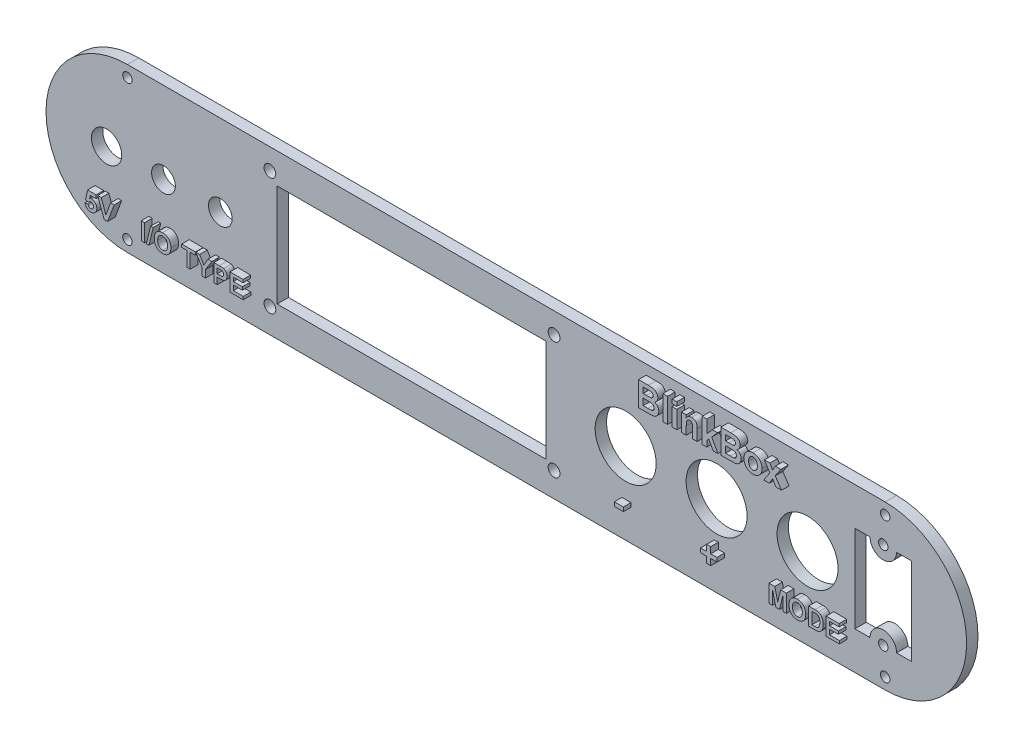
SolidWorks part; units mm, degrees
ref_plane "Front Plane" through (0, 0, 0) normal (0, 0, 1) x (1, 0, 0)
ref_plane "Top Plane" through (0, 0, 0) normal (0, 1, 0) x (1, 0, 0)
ref_plane "Right Plane" through (0, 0, 0) normal (1, 0, 0) x (0, 0, -1)
sketch "Sketch3" plane through (0, 0, 0) normal (0, 0, 1) x (1, 0, 0)
  circle A0 centre (0, 0) radius 2.5
  dimension "D1" = 5
sketch "Sketch1" plane through (0, 0, 0) normal (0, 0, 1) x (1, 0, 0)
  line L0 (-100, 0) -> (100, 0) construction
  line L1 (-100, 0) -> (100, 0) construction
  line L2 (-100, 21.5) -> (100, 21.5)
  line L3 (-100, -21.5) -> (100, -21.5)
  arc A0 (-100, 21.5) -> (-100, -21.5) centre (-100, 0) ccw
  arc A1 (100, -21.5) -> (100, 21.5) centre (100, 0) ccw
  point P2 (0, 0)
  dimension "D1" = 200
  dimension "D2" = 43
extrude "Boss-Extrude1" add sketch "Sketch1" along normal blind 3
sketch "Sketch2" plane through (0, 0, 3) normal (0, 0, 1) x (1, 0, 0)
  line L0 (-121.5, 0) -> (-105.5, 0) construction
  line L1 (-60.5, 13.5) -> (10.5, 13.5)
  line L2 (-60.5, 13.5) -> (-60.5, -13.5)
  line L3 (-60.5, -13.5) -> (10.5, -13.5)
  line L4 (10.5, 13.5) -> (10.5, -13.5)
  line L5 (-60.5, 13.5) -> (10.5, -13.5) construction
  line L6 (-60.5, -13.5) -> (10.5, 13.5) construction
  line L7 (-105.5, 0) -> (-90.5, 0) construction
  line L8 (-90.5, 0) -> (-75.5, 0) construction
  line L9 (-75.5, 0) -> (-60.5, 0) construction
  line L10 (31.5, 0) -> (55.5, 0) construction
  line L11 (55.5, 0) -> (79.5, 0) construction
  circle A0 centre (-105.5, 0) radius 4
  circle A1 centre (-90.5, 0) radius 3.135
  circle A2 centre (-75.5, 0) radius 3.135
  circle A3 centre (55.5, 0) radius 8.05
  circle A4 centre (31.5, 0) radius 8.05
  circle A5 centre (79.5, 0) radius 8.05
  arc A6 (-100, 21.5) -> (-100, -21.5) centre (-100, 0) ccw construction
  point P0 (-25, 0)
  dimension "D1" = 71
  dimension "D3" = 8
  dimension "D4" = 6.27
  dimension "D7" = 16.1
  dimension "D2" = 27
  dimension "D5" = 15
  dimension "D6" = 15
  dimension "D8" = 24
  dimension "D9" = 25
  dimension "D10" = 21
extrude "Cut-Extrude1" cut sketch "Sketch2" against normal through all both and the other way through all
sketch "Sketch4" plane through (0, 0, 3) normal (0, 0, 1) x (1, 0, 0)
  line L2 (-21.65, -11.5) -> (-28.15, -11.5)
  line L3 (-28.15, -12.5) -> (-21.65, -12.5)
  line L4 (15.1, 18.5) -> (-64.9, 18.5)
  line L5 (-64.9, 18.5) -> (-64.9, -17.5)
  line L6 (-64.9, -17.5) -> (15.1, -17.5)
  line L7 (15.1, -17.5) -> (15.1, 18.5)
  line L8 (15.1, 18.5) -> (-64.9, 18.5)
  line L9 (-64.9, 18.5) -> (-64.9, -17.5)
  line L10 (-64.9, -17.5) -> (15.1, -17.5)
  line L11 (15.1, -17.5) -> (15.1, 18.5)
  line L12 (-21.65, -11.5) -> (-28.15, -11.5)
  line L13 (-28.15, -12.5) -> (-21.65, -12.5)
  line L14 (7.35, 12.5) -> (0.85, 12.5)
  line L15 (0.85, 11.5) -> (7.35, 11.5)
  line L16 (7.35, 12.5) -> (0.85, 12.5)
  line L17 (0.85, 11.5) -> (7.35, 11.5)
  line L18 (7.35, -11.5) -> (0.85, -11.5)
  line L19 (0.85, -12.5) -> (7.35, -12.5)
  line L20 (7.35, -11.5) -> (0.85, -11.5)
  line L21 (0.85, -12.5) -> (7.35, -12.5)
  line L22 (-50.65, -11.5) -> (-57.15, -11.5)
  line L23 (-57.15, -12.5) -> (-50.65, -12.5)
  line L24 (-50.65, -11.5) -> (-57.15, -11.5)
  line L25 (-57.15, -12.5) -> (-50.65, -12.5)
  line L26 (-21.65, 12.5) -> (-28.15, 12.5)
  line L27 (-28.15, 11.5) -> (-21.65, 11.5)
  line L28 (-21.65, 12.5) -> (-28.15, 12.5)
  line L29 (-28.15, 11.5) -> (-21.65, 11.5)
  line L30 (-50.65, 12.5) -> (-57.15, 12.5)
  line L31 (-57.15, 11.5) -> (-50.65, 11.5)
  line L32 (-50.65, 12.5) -> (-57.15, 12.5)
  line L33 (-57.15, 11.5) -> (-50.65, 11.5)
  line L48 (10.5, 13.5) -> (-60.5, 13.5) construction
  line L49 (-60.5, 13.5) -> (-60.5, -13.5) construction
  circle A0 centre (-90.5, 0) radius 7
  circle A1 centre (-105.5, 0) radius 5.5
  circle A2 centre (-105.5, 0) radius 4 construction
  circle A3 centre (-75.5, 0) radius 5
  circle A4 centre (-75.5, 0) radius 3.135 construction
  circle A6 centre (12.6, -15) radius 1.25
  circle A7 centre (12.6, -15) radius 1.25
  circle A8 centre (12.6, 16) radius 1.25
  circle A9 centre (12.6, 16) radius 1.25
  circle A10 centre (-62.4, -15) radius 1.25
  circle A11 centre (-62.4, -15) radius 1.25
  circle A12 centre (-62.4, 16) radius 1.25
  circle A13 centre (-62.4, 16) radius 1.25
  circle A14 centre (-39.12, 16) radius 0.5
  circle A15 centre (-39.12, 16) radius 0.5
  circle A16 centre (-41.66, 16) radius 0.5
  circle A17 centre (-41.66, 16) radius 0.5
  circle A18 centre (-44.2, 16) radius 0.5
  circle A19 centre (-44.2, 16) radius 0.5
  circle A20 centre (-46.74, 16) radius 0.5
  circle A21 centre (-46.74, 16) radius 0.5
  circle A22 centre (-49.28, 16) radius 0.5
  circle A23 centre (-49.28, 16) radius 0.5
  circle A24 centre (-51.82, 16) radius 0.5
  circle A25 centre (-51.82, 16) radius 0.5
  circle A26 centre (-54.36, 16) radius 0.5
  circle A27 centre (-54.36, 16) radius 0.5
  circle A28 centre (-56.9, 16) radius 0.5
  circle A29 centre (-56.9, 16) radius 0.5
  circle A30 centre (-18.8, 16) radius 0.5
  circle A31 centre (-18.8, 16) radius 0.5
  circle A32 centre (-21.34, 16) radius 0.5
  circle A33 centre (-21.34, 16) radius 0.5
  circle A34 centre (-23.88, 16) radius 0.5
  circle A35 centre (-23.88, 16) radius 0.5
  circle A36 centre (-26.42, 16) radius 0.5
  circle A37 centre (-26.42, 16) radius 0.5
  circle A38 centre (-28.96, 16) radius 0.5
  circle A39 centre (-28.96, 16) radius 0.5
  circle A40 centre (-31.5, 16) radius 0.5
  circle A41 centre (-31.5, 16) radius 0.5
  circle A42 centre (-34.04, 16) radius 0.5
  circle A43 centre (-34.04, 16) radius 0.5
  circle A44 centre (-36.58, 16) radius 0.5
  circle A45 centre (-36.58, 16) radius 0.5
  arc A47 (-21.65, -12.5) -> (-21.65, -11.5) centre (-21.65, -12) ccw
  arc A48 (-28.15, -11.5) -> (-28.15, -12.5) centre (-28.15, -12) ccw
  arc A49 (-21.65, -12.5) -> (-21.65, -11.5) centre (-21.65, -12) ccw
  arc A50 (-28.15, -11.5) -> (-28.15, -12.5) centre (-28.15, -12) ccw
  arc A51 (7.35, 11.5) -> (7.35, 12.5) centre (7.35, 12) ccw
  arc A52 (0.85, 12.5) -> (0.85, 11.5) centre (0.85, 12) ccw
  arc A53 (7.35, 11.5) -> (7.35, 12.5) centre (7.35, 12) ccw
  arc A54 (0.85, 12.5) -> (0.85, 11.5) centre (0.85, 12) ccw
  arc A55 (7.35, -12.5) -> (7.35, -11.5) centre (7.35, -12) ccw
  arc A56 (0.85, -11.5) -> (0.85, -12.5) centre (0.85, -12) ccw
  arc A57 (7.35, -12.5) -> (7.35, -11.5) centre (7.35, -12) ccw
  arc A58 (0.85, -11.5) -> (0.85, -12.5) centre (0.85, -12) ccw
  arc A59 (-50.65, -12.5) -> (-50.65, -11.5) centre (-50.65, -12) ccw
  arc A60 (-57.15, -11.5) -> (-57.15, -12.5) centre (-57.15, -12) ccw
  arc A61 (-50.65, -12.5) -> (-50.65, -11.5) centre (-50.65, -12) ccw
  arc A62 (-57.15, -11.5) -> (-57.15, -12.5) centre (-57.15, -12) ccw
  arc A63 (-21.65, 11.5) -> (-21.65, 12.5) centre (-21.65, 12) ccw
  arc A64 (-28.15, 12.5) -> (-28.15, 11.5) centre (-28.15, 12) ccw
  arc A65 (-21.65, 11.5) -> (-21.65, 12.5) centre (-21.65, 12) ccw
  arc A66 (-28.15, 12.5) -> (-28.15, 11.5) centre (-28.15, 12) ccw
  arc A67 (-50.65, 11.5) -> (-50.65, 12.5) centre (-50.65, 12) ccw
  arc A68 (-57.15, 12.5) -> (-57.15, 11.5) centre (-57.15, 12) ccw
  arc A69 (-50.65, 11.5) -> (-50.65, 12.5) centre (-50.65, 12) ccw
  arc A70 (-57.15, 12.5) -> (-57.15, 11.5) centre (-57.15, 12) ccw
  circle A101 centre (-25, 0) radius 2.5
  circle A102 centre (0, 0) radius 2.5 construction
  point P116 (-25, 13.5)
  point P120 (-60.5, 0)
  dimension "D1" = 14
  dimension "D2" = 11
  dimension "D3" = 10
  dimension "D4" = 0
  dimension "D5" = 0
  dimension "D6" = 0
  dimension "D7" = 0
  dimension "D8" = 0
  dimension "D9" = 0
  dimension "D10" = 0
  dimension "D11" = 0
  dimension "D12" = 0
  dimension "D13" = 0
  dimension "D14" = 0
  dimension "D15" = 0
  dimension "D16" = 0
  dimension "D17" = 0
  dimension "D18" = 0
  dimension "D19" = 0
  dimension "D20" = 0
  dimension "D21" = 0
  dimension "D22" = 0
  dimension "D23" = 0
  dimension "D24" = 0
  dimension "D25" = 0
  dimension "D26" = 0
  dimension "D27" = 0
  dimension "D28" = 0
  dimension "D29" = 0
  dimension "D30" = 0
sketch "Sketch5" plane through (0, 0, 3) normal (0, 0, 1) x (1, 0, 0)
  circle A0 centre (-62.4, 16) radius 1.55
  circle A1 centre (-62.4, -15) radius 1.55
  circle A2 centre (12.6, -15) radius 1.55
  circle A3 centre (12.6, 16) radius 1.55
  circle A4 centre (-62.4, 16) radius 2.5 construction
  circle A5 centre (-62.4, -15) radius 2.5 construction
  circle A6 centre (12.6, -15) radius 2.5 construction
  circle A7 centre (12.6, 16) radius 2.5 construction
  dimension "D1" = 3.1
extrude "Cut-Extrude2" cut sketch "Sketch5" against normal through all both and the other way through all
sketch "Sketch6" plane through (0, 0, 3) normal (0, 0, 1) x (1, 0, 0)
  line L0 (99.5, 11.5) -> (99.5, -11.5) construction
  line L2 (92, 11.5) -> (107, 11.5)
  line L3 (92, 11.5) -> (92, -11.5)
  line L4 (92, -11.5) -> (107, -11.5)
  line L5 (107, 11.5) -> (107, -11.5)
  circle A0 centre (99.5, 11.5) radius 1.25
  circle A1 centre (99.5, -11.5) radius 1.25
  arc A2 (96, 11.5) -> (103, 11.5) centre (99.5, 11.5) ccw
  arc A3 (96, -11.5) -> (103, -11.5) centre (99.5, -11.5) cw
  circle A4 centre (79.5, 0) radius 8.05
  circle A5 centre (79.5, 0) radius 8.05 construction
  point P4 (99.5, 0)
  point P10 (99.5, 11.5)
  point P23 (103, 11.5)
  dimension "D1" = 2.5
  dimension "D5" = 3.5
  dimension "D6" = 20
  dimension "D2" = 23
  dimension "D3" = 15
extrude "Cut-Extrude5" cut sketch "Sketch6" against normal through all both and the other way through all contours L0 A2 L2 L3 L4 A3 | A2 L0 A3 L4 L5 L2 | L0 A1 L4 | A1 L0 L4 | L4 A1 | A0
sketch "Sketch8" plane through (0, 0, 3) normal (0, 0, 1) x (1, 0, 0)
  line L0 (-100, 21.5) -> (-100, 18.5) construction
  line L1 (-100, -21.5) -> (-100, -18.5) construction
  line L2 (100, 21.5) -> (100, 18.5) construction
  line L3 (100, -21.5) -> (100, -18.5) construction
  circle A0 centre (-100, 18.5) radius 1.25
  circle A1 centre (-100, -18.5) radius 1.25
  circle A2 centre (100, 18.5) radius 1.25
  circle A3 centre (100, -18.5) radius 1.25
  dimension "D1" = 2.5
  dimension "D2" = 3
extrude "Cut-Extrude4" cut sketch "Sketch8" against normal through all both and the other way through all
sketch "Sketch9" plane through (0, 0, 3) normal (0, 0, 1) x (1, 0, 0)
  line L0 (-105.5, 0) -> (-105.5, -15) construction
  line L1 (-90.5, 0) -> (-90.5, -15) construction
  line L2 (-75.5, 0) -> (-75.5, -15) construction
  line L3 (31.5, 0) -> (31.5, -15) construction
  line L4 (55.5, 0) -> (55.5, -15) construction
  line L5 (79.5, 0) -> (79.5, -15) construction
  line L6 (22.9411, -15) -> (40.0589, -15) construction
  line L7 (46.9411, -15) -> (64.0589, -15) construction
  line L8 (70.9411, -15) -> (88.0589, -15) construction
  line L9 (-84.0589, -15) -> (-66.9411, -15) construction
  line L10 (-99.0589, -15) -> (-81.9411, -15) construction
  line L11 (-114.0589, -15) -> (-96.9411, -15) construction
  line L12 (100, 21.5) -> (-100, 21.5) construction
  line L13 (16.7293, 12.5) -> (94.2707, 12.5) construction
  text T0 "5V" font "Arial" height in points 18
  text T1 "I/O" font "Arial" height in points 18
  text T2 "TYPE" font "Arial" height in points 18
  text T3 "MODE" font "Arial" height in points 18
  text T4 "+" font "Arial" height in points 25
  text T5 "-" font "Arial" height in points 25
  text T6 "BlinkBox" font "Arial" height in points 25
  point P21 (31.5, -15)
  point P24 (55.5, -15)
  point P27 (79.5, -15)
  point P30 (-75.5, -15)
  point P33 (-90.5, -15)
  point P36 (-105.5, -15)
  point P42 (55.5, 12.5)
  dimension "D1" = 15
  dimension "D2" = 9
extrude "Boss-Extrude2" add sketch "Sketch9" along normal blind 2
